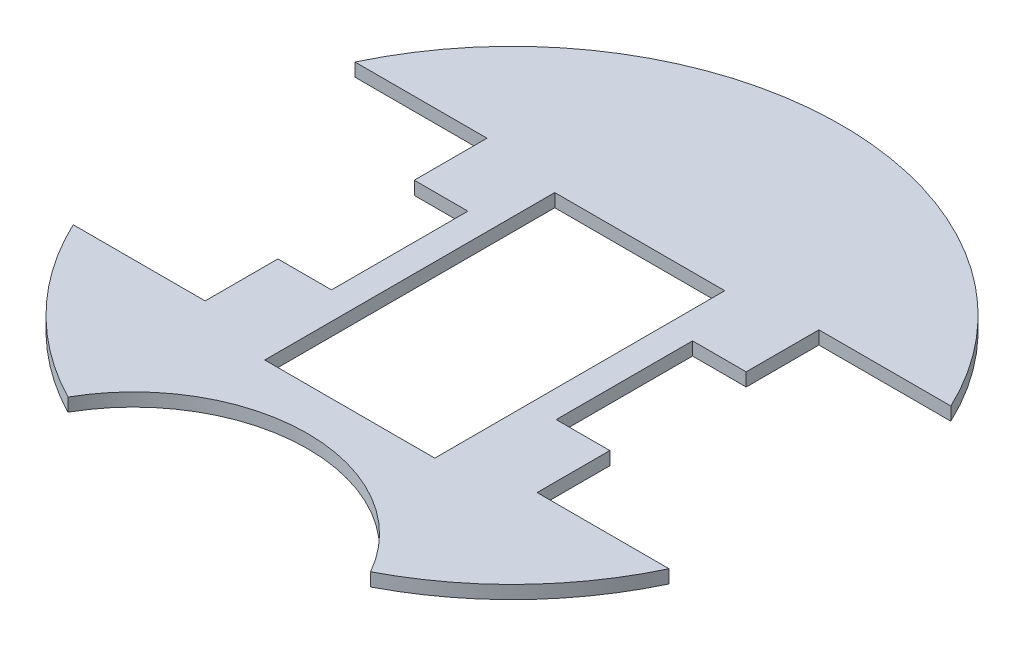
SolidWorks part; units mm, degrees
ref_plane "Front Plane" through (0, 0, 0) normal (0, 0, 1) x (1, 0, 0)
ref_plane "Top Plane" through (0, 0, 0) normal (0, 1, 0) x (1, 0, 0)
ref_plane "Right Plane" through (0, 0, 0) normal (1, 0, 0) x (0, 0, -1)
sketch "Sketch1" plane through (0, 0, 0) normal (0, 1, 0) x (1, 0, 0)
  line L0 (0, -83.2398) -> (-33.2911, -64.4046) construction
  line L1 (0, -83.2398) -> (0, 0) construction
  arc A0 (33.2911, -64.4046) -> (-33.2911, -64.4046) centre (0, 0) ccw
  arc A1 (33.2911, -64.4046) -> (-33.2911, -64.4046) centre (0, -83.2398) ccw
  dimension "D1" = 145
  dimension "D2" = 76.5
  dimension "D3" = 60.5
extrude "Boss-Extrude1" add sketch "Sketch1" along normal blind 2.9
sketch "solenoid placement" plane through (0, 2.9, 0) normal (0, 1, 0) x (1, 0, 0)
  line L4 (-18.7, -35.7) -> (18.7, -35.7)
  line L5 (18.7, -35.7) -> (18.7, 28.1)
  line L6 (18.7, 28.1) -> (-18.7, 28.1)
  line L7 (-18.7, 28.1) -> (-18.7, -35.7)
  line L8 (-18.7, -35.7) -> (18.7, -35.7)
  line L9 (18.7, -35.7) -> (18.7, 28.1)
  line L10 (18.7, 28.1) -> (-18.7, 28.1)
  line L11 (-18.7, 28.1) -> (-18.7, -35.7)
  circle A1 centre (0, 0) radius 72.5 construction
  arc A2 (33.2911, -64.4046) -> (-33.2911, -64.4046) centre (0, 0) ccw construction
  dimension "D1" = 0
extrude "Cut-Extrude1" cut sketch "solenoid placement" against normal through all
sketch "Sketch2" plane through (0, 2.9, 0) normal (0, 1, 0) x (1, 0, 0)
  line L0 (0, 0) -> (0, 72.5) construction
  line L1 (-36.51, -15) -> (-24.71, -15)
  line L2 (36.51, -31) -> (65.5382, -31)
  line L3 (-36.51, 15) -> (-24.71, 15)
  line L4 (-24.71, -15) -> (-24.71, 15)
  line L5 (-36.51, 15) -> (-36.51, 31)
  line L6 (-36.51, 31) -> (-65.5382, 31)
  line L7 (-36.51, -15) -> (-36.51, -31)
  line L8 (-36.51, -31) -> (-65.5382, -31)
  line L9 (36.51, -15) -> (36.51, -31)
  line L10 (36.51, 31) -> (65.5382, 31)
  line L11 (36.51, 15) -> (36.51, 31)
  line L12 (24.71, -15) -> (24.71, 15)
  line L13 (36.51, 15) -> (24.71, 15)
  line L14 (36.51, -15) -> (24.71, -15)
  arc A0 (33.2911, -64.4046) -> (-33.2911, -64.4046) centre (0, 0) ccw construction
  arc A1 (65.5382, 31) -> (65.5382, -31) centre (0, 0) cw
  arc A2 (-65.5382, 31) -> (-65.5382, -31) centre (0, 0) ccw
  dimension "D1" = 62
extrude "Cut-Extrude2" cut sketch "Sketch2" against normal through all
equation "\"smallPulleyTeeth\"= 15"
equation "\"largePulleyTeeth\"= 40"
equation "\"eighthThick\"= 2.9mm"
equation "\"sixteenthThick\"= 1.7mm"
equation "\"quarterThick\"=5.9mm"
equation "\"OD\"= 145mm"
equation "\"puckAngle\"= 60.5deg"
equation "\"D1@Sketch1\"=\"OD\""
equation "\"puckDiam\"= 76.5mm"
equation "\"D2@Sketch1\"=\"puckDiam\""
equation "\"D3@Sketch1\"=\"puckAngle\""
equation "\"D1@Boss-Extrude1\"=\"eighthThick\""
equation "\"axlePress\"= 5.9mm"
equation "\"press\"= 0.2mm"
equation "\"wheelClear\"= 0.3mm"
equation "\"10-32clear\"= 4.5mm"
equation "\"6-32clear\"= 3.3mm"
equation "\"8-32clear\"= 4.0mm"
equation "\"wheelHeight\"= 24mm"
equation "\"wheelWell\"= 62mm"
equation "\"D1@Sketch2\"=\"wheelWell\""
